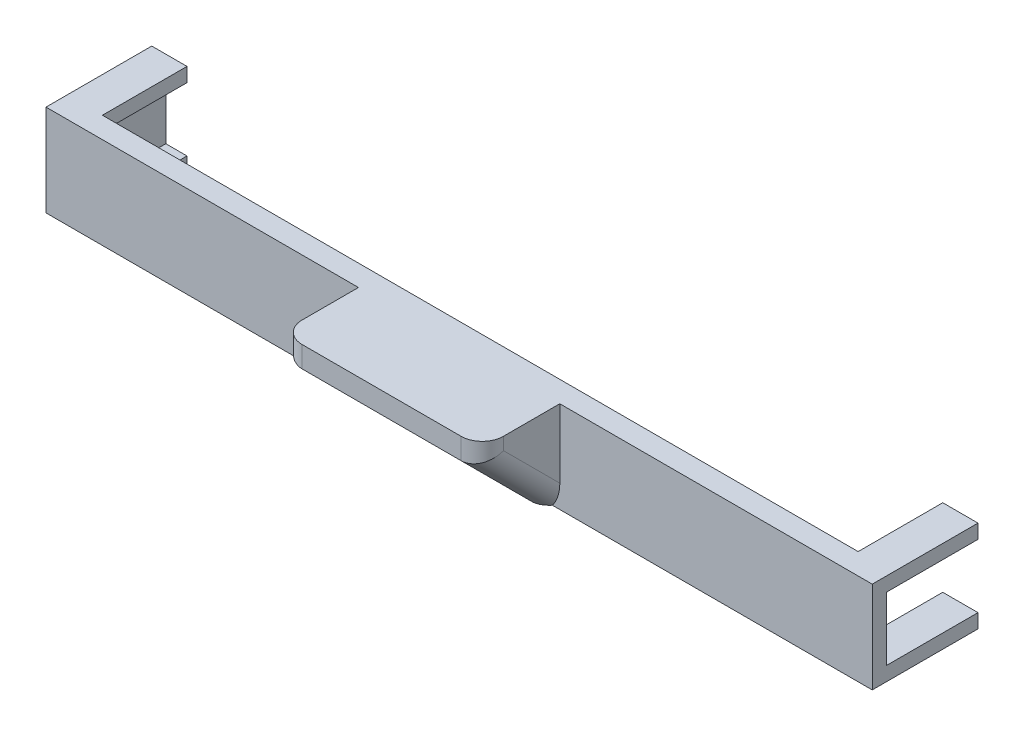
SolidWorks part; units mm, degrees
ref_plane "Front Plane" through (0, 0, 0) normal (0, 0, 1) x (1, 0, 0)
ref_plane "Top Plane" through (0, 0, 0) normal (0, 1, 0) x (1, 0, 0)
ref_plane "Right Plane" through (0, 0, 0) normal (1, 0, 0) x (0, 0, -1)
sketch "Sketch1" plane through (0, 0, 0) normal (0, 0, 1) x (1, 0, 0)
  line L1 (-70.6544, -24.4975) -> (46.5456, -24.4975)
  line L2 (-70.6544, -24.4975) -> (-70.6544, -37.4975)
  line L3 (-70.6544, -37.4975) -> (46.5456, -37.4975)
  line L4 (46.5456, -24.4975) -> (46.5456, -37.4975)
  line L5 (-68.6544, -26.4975) -> (44.5456, -26.4975)
  line L6 (-68.6544, -26.4975) -> (-68.6544, -35.4975)
  line L7 (-68.6544, -35.4975) -> (44.5456, -35.4975)
  line L8 (44.5456, -26.4975) -> (44.5456, -35.4975)
  dimension "D1" = 117.2
  dimension "D2" = 13
  dimension "D3" = 2
  dimension "D4" = 2
  dimension "D5" = 2
  dimension "D6" = 2
extrude "Boss-Extrude1" add sketch "Sketch1" along normal blind 15
sketch "Sketch2" plane through (0, 0, 15) normal (0, 0, 1) x (1, 0, 0)
  line L1 (-70.6544, -24.4975) -> (46.5456, -24.4975)
  line L2 (-70.6544, -24.4975) -> (-70.6544, -37.4975)
  line L3 (-70.6544, -37.4975) -> (46.5456, -37.4975)
  line L4 (46.5456, -24.4975) -> (46.5456, -37.4975)
extrude "Boss-Extrude2" add sketch "Sketch2" against normal blind 2
sketch "Sketch3" plane through (0, -37.4975, 0) normal (0, -1, 0) x (1, 0, 0)
  line L0 (-70.6544, 0) -> (46.5456, 0) construction
  line L1 (-65.6544, 0) -> (41.5456, 0)
  line L2 (-65.6544, 0) -> (-65.6544, 12)
  line L3 (-65.6544, 12) -> (41.5456, 12)
  line L4 (41.5456, 0) -> (41.5456, 12)
  line L5 (-70.6544, 15) -> (-70.6544, 0) construction
  line L6 (46.5456, 15) -> (46.5456, 0) construction
  line L7 (-70.6544, 15) -> (46.5456, 15) construction
  dimension "D1" = 5
  dimension "D2" = 5
  dimension "D3" = 3
extrude "Cut-Extrude1" cut sketch "Sketch3" against normal through all
sketch "Sketch4" plane through (46.5456, 0, 0) normal (1, 0, 0) x (0, 0, -1)
  line L0 (0, -37.4975) -> (0, -24.4975) construction
  line L1 (0, -35.4975) -> (-13, -35.4975)
  line L2 (0, -35.4975) -> (0, -26.4975)
  line L3 (0, -26.4975) -> (-13, -26.4975)
  line L4 (-13, -35.4975) -> (-13, -26.4975)
  line L5 (-15, -37.4975) -> (0, -37.4975) construction
  line L6 (-15, -24.4975) -> (0, -24.4975) construction
  line L7 (-15, -37.4975) -> (-15, -24.4975) construction
  dimension "D1" = 2
  dimension "D2" = 2
  dimension "D3" = 2
extrude "Cut-Extrude2" cut sketch "Sketch4" against normal up to next
sketch "Sketch5" plane through (0, 0, 15) normal (0, 0, 1) x (1, 0, 0)
  line L0 (-26.3344, -24.4975) -> (-26.3344, -37.4975) construction
  line L1 (46.5456, -24.4975) -> (-70.6544, -24.4975) construction
  line L2 (-70.6544, -37.4975) -> (46.5456, -37.4975) construction
  line L3 (-70.6544, -24.4975) -> (-70.6544, -37.4975) construction
  line L4 (2.2256, -37.4975) -> (2.2256, -24.4975) construction
  line L5 (46.5456, -37.4975) -> (46.5456, -24.4975) construction
  line L7 (-26.3344, -24.4975) -> (2.2256, -24.4975)
  line L8 (-26.3344, -24.4975) -> (-26.3344, -37.4975)
  line L9 (-26.3344, -37.4975) -> (2.2256, -37.4975)
  line L10 (2.2256, -24.4975) -> (2.2256, -37.4975)
  dimension "D1" = 44.32
  dimension "D2" = 44.32
extrude "Boss-Extrude3" add sketch "Sketch5" along normal blind 11
chamfer "Chamfer1" distance 10 angle 45 1 edges at (-12.0544, -37.4975, 26)
fillet "Fillet1" radius 3 2 edges at (-26.3344, -25.9975, 26) (-26.3344, -32.4975, 21)
fillet "Fillet2" radius 3 2 edges at (2.2256, -25.9975, 26) (2.2256, -32.4975, 21)
sketch "Sketch6" plane through (0, -24.4975, 0) normal (0, 1, 0) x (1, 0, 0)
  line L0 (41.5456, -12) -> (-65.6544, -12) construction
  line L1 (-0.7744, -23) -> (-23.3344, -23)
  line L2 (-0.7744, -23) -> (-0.7744, -12)
  line L3 (-0.7744, -12) -> (-23.3344, -12)
  line L4 (-23.3344, -23) -> (-23.3344, -12)
  line L5 (2.2256, -23) -> (2.2256, -15) construction
  line L6 (-26.3344, -23) -> (-26.3344, -15) construction
  line L7 (-0.7744, -26) -> (-23.3344, -26) construction
  line L8 (-23.3344, -12) -> (-0.7744, -12)
  dimension "D1" = 3
  dimension "D2" = 3
  dimension "D3" = 3
